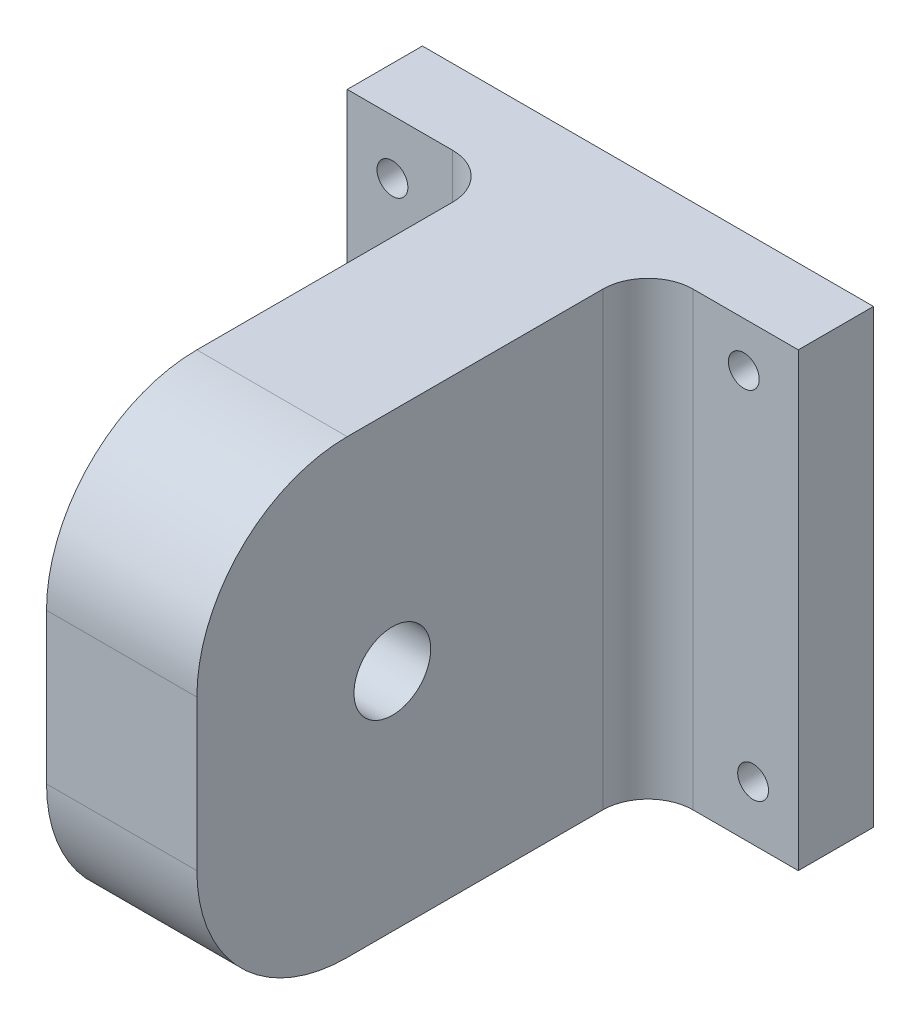
SolidWorks part; units mm, degrees
ref_plane "Front Plane" through (0, 0, 0) normal (0, 0, 1) x (1, 0, 0)
ref_plane "Top Plane" through (0, 0, 0) normal (0, 1, 0) x (1, 0, 0)
ref_plane "Right Plane" through (0, 0, 0) normal (1, 0, 0) x (0, 0, -1)
sketch "Sketch1" plane through (0, 0, 0) normal (0, 0, 1) x (1, 0, 0)
  line L1 (-15, 15) -> (15, 15)
  line L2 (-15, 15) -> (-15, -15)
  line L3 (-15, -15) -> (15, -15)
  line L4 (15, 15) -> (15, -15)
  line L5 (-15, 15) -> (15, -15) construction
  line L6 (-15, -15) -> (15, 15) construction
  point P0 (0, 0)
  dimension "D1" = 30
  dimension "D2" = 30
extrude "Boss-Extrude2" add sketch "Sketch1" along normal blind 5
sketch "Sketch3" plane through (0, 0, 5) normal (0, 0, 1) x (1, 0, 0)
  circle A0 centre (-11.994, 11.3751) radius 1.0262
  circle A1 centre (11.3751, 11.994) radius 1.0262
  circle A2 centre (11.994, -11.3751) radius 1.0262
  circle A3 centre (-11.3751, -11.994) radius 1.0262
  point P11 (0, 0)
  dimension "D1" = 4
extrude "Cut-Extrude1" cut sketch "Sketch3" against normal blind 5
sketch "Sketch4" plane through (0, 0, 5) normal (0, 0, 1) x (1, 0, 0)
  line L0 (-15, -15) -> (15, -15) construction
  line L1 (5, 15) -> (-5, 15)
  line L2 (5, 15) -> (5, -15)
  line L3 (5, -15) -> (-5, -15)
  line L4 (-5, 15) -> (-5, -15)
  line L5 (5, 15) -> (-5, -15) construction
  line L6 (5, -15) -> (-5, 15) construction
  point P0 (0, 0)
  dimension "D1" = 10
extrude "Boss-Extrude3" add sketch "Sketch4" along normal blind 30
sketch "Sketch5" plane through (5, 0, 0) normal (1, 0, 0) x (0, 0, -1)
  line L0 (-35, 0) -> (-22, 0) construction
  line L1 (-35, -15) -> (-35, 15) construction
  circle A0 centre (-22, 0) radius 2.55
  dimension "D2" = 5.1
  dimension "D1" = 13
extrude "Cut-Extrude2" cut sketch "Sketch5" against normal blind 30
fillet "Fillet1" radius 10 1 edges at (0, -15, 35)
fillet "Fillet2" radius 10 1 edges at (0, 15, 35)
fillet "Fillet4" radius 3 1 edges at (5, 0, 5)
fillet "Fillet5" radius 3 1 edges at (-5, 0, 5)
